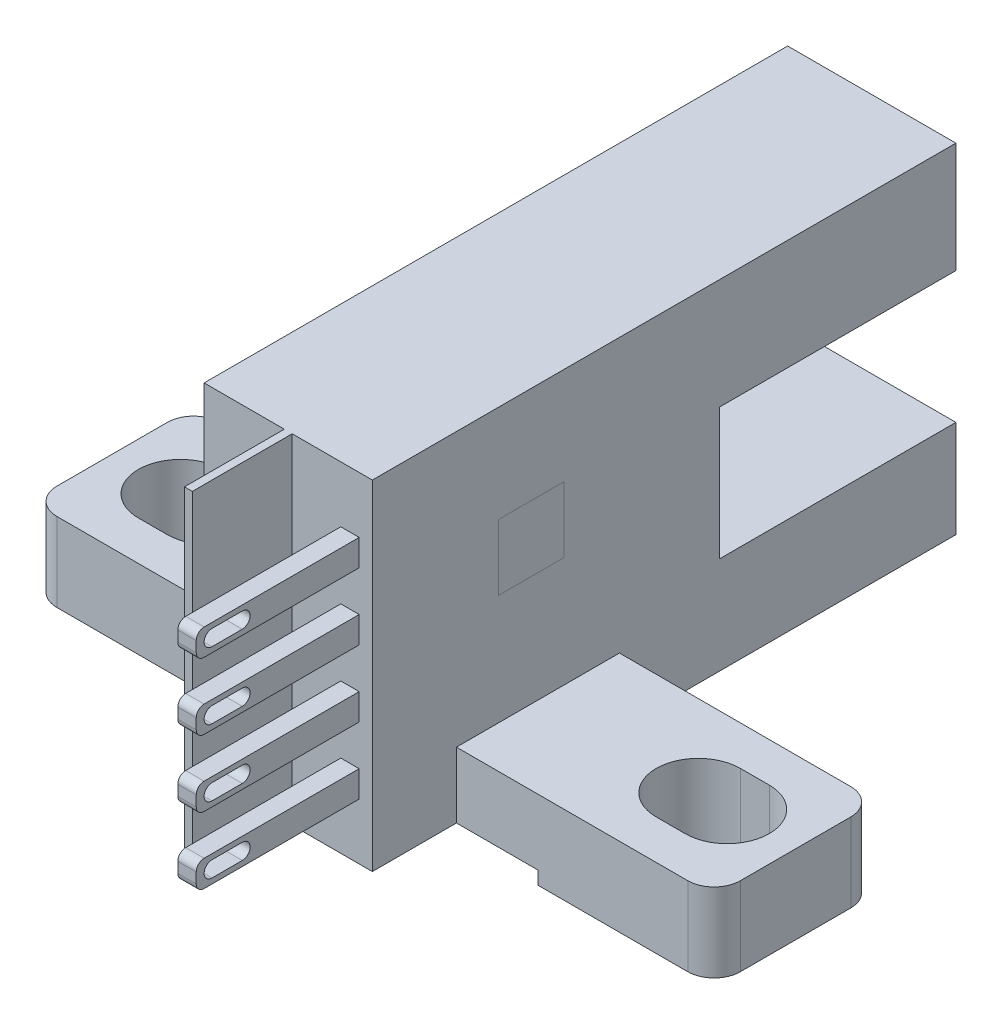
SolidWorks part; units mm, degrees
ref_plane "Front" through (0, 0, 0) normal (0, 0, 1) x (1, 0, 0)
ref_plane "Top" through (0, 0, 0) normal (0, 1, 0) x (1, 0, 0)
ref_plane "Right" through (0, 0, 0) normal (1, 0, 0) x (0, 0, -1)
sketch "Sketch2" plane through (0, 0, 0) normal (0, 1, 0) x (1, 0, 0)
  line L0 (-10.4, 0) -> (-9.3, 0) construction
  line L1 (13, -3.1) -> (-13, -3.1)
  line L2 (13, -3.1) -> (13, 3.1)
  line L3 (13, 3.1) -> (-13, 3.1)
  line L4 (-13, -3.1) -> (-13, 3.1)
  line L5 (13, -3.1) -> (-13, 3.1) construction
  line L6 (13, 3.1) -> (-13, -3.1) construction
  line L7 (-10.4, 1.6) -> (-9.3, 1.6)
  line L8 (-10.4, -1.6) -> (-9.3, -1.6)
  line L9 (0, 3.1) -> (0, 0) construction
  line L10 (10.4, 0) -> (9.3, 0) construction
  line L11 (10.4, 1.6) -> (9.3, 1.6)
  line L12 (10.4, -1.6) -> (9.3, -1.6)
  arc A0 (-10.4, 1.6) -> (-10.4, -1.6) centre (-10.4, 0) ccw
  arc A1 (-9.3, -1.6) -> (-9.3, 1.6) centre (-9.3, 0) ccw
  arc A2 (10.4, 1.6) -> (10.4, -1.6) centre (10.4, 0) cw
  arc A3 (9.3, -1.6) -> (9.3, 1.6) centre (9.3, 0) cw
  point P0 (0, 0)
  point P8 (-9.85, 0)
  point P13 (-7.7, 0)
  point P14 (-12, 0)
  point P19 (9.85, 0)
  dimension "D3" = 1.6
  dimension "D1" = 26
  dimension "D2" = 6.2
  dimension "D4" = 4.3
  dimension "D5" = 12
extrude "Boss-Extrude1" add sketch "Sketch2" along normal blind 3
sketch "Sketch3" plane through (0, 0, 0) normal (0, 1, 0) x (1, 0, 0)
  line L0 (13, -3.1) -> (13, 3.1) construction
  line L1 (-3.2, 15.9) -> (3.2, 15.9)
  line L2 (-3.2, 15.9) -> (-3.2, -6.3)
  line L3 (-3.2, -6.3) -> (3.2, -6.3)
  line L4 (3.2, 15.9) -> (3.2, -6.3)
  line L5 (-3.2, 15.9) -> (3.2, -6.3) construction
  line L6 (-3.2, -6.3) -> (3.2, 15.9) construction
  point P0 (0, 4.8)
  point P5 (0, 0)
  point P9 (13, 0)
  dimension "D1" = 6.4
  dimension "D2" = 22.2
  dimension "D3" = 6.3
extrude "Boss-Extrude2" add sketch "Sketch3" along normal blind 13.4
sketch "Sketch4" plane through (3.2, 0, 0) normal (1, 0, 0) x (0, 0, -1)
  line L0 (15.9, 13.4) -> (15.9, 0) construction
  line L1 (6.9, 4.2) -> (15.9, 4.2)
  line L2 (6.9, 4.2) -> (6.9, 9.2)
  line L3 (6.9, 9.2) -> (15.9, 9.2)
  line L4 (15.9, 4.2) -> (15.9, 9.2)
  line L5 (6.9, 4.2) -> (15.9, 9.2) construction
  line L6 (6.9, 9.2) -> (15.9, 4.2) construction
  line L7 (-6.3, 13.4) -> (-6.3, 0) construction
  point P0 (11.4, 6.7)
  point P7 (0, 0)
  point P10 (-6.3, 6.7)
  dimension "D1" = 5
  dimension "D2" = 9
extrude "Cut-Extrude1" cut sketch "Sketch4" against normal through all
sketch "Sketch5" plane through (3.2, 0, 0) normal (1, 0, 0) x (0, 0, -1)
  line L0 (6.9, 9.2) -> (6.9, 4.2) construction
  line L1 (1, 9.7) -> (-1.5, 9.7)
  line L2 (1, 9.7) -> (1, 7.2)
  line L3 (1, 7.2) -> (-1.5, 7.2)
  line L4 (-1.5, 9.7) -> (-1.5, 7.2)
  point P6 (6.9, 6.7)
  dimension "D1" = 2.5
  dimension "D2" = 8.4
  dimension "D3" = 3
split line "Split Line1"
fillet "Fillet1" radius 1 4 edges at (-13, 1.5, -3.1) (-13, 1.5, 3.1) (13, 1.5, -3.1) (13, 1.5, 3.1)
sketch "Sketch6" plane through (0, 0, 0) normal (0, 0, 1) x (1, 0, 0)
  line L0 (-12, 0) -> (-3.2, 0) construction
  line L1 (6.3, 0.5) -> (-6.3, 0.5)
  line L2 (6.3, 0.5) -> (6.3, 0)
  line L3 (6.3, 0) -> (-6.3, 0)
  line L4 (-6.3, 0.5) -> (-6.3, 0)
  line L5 (6.3, 0.5) -> (-6.3, 0) construction
  line L6 (6.3, 0) -> (-6.3, 0.5) construction
  point P0 (0, 0.25)
  point P7 (0, 0)
  dimension "D1" = 12.6
  dimension "D2" = 0.5
extrude "Cut-Extrude2" cut sketch "Sketch6" against normal through all both and the other way through all
sketch "Sketch8" plane through (0, 13.4, 0) normal (0, 1, 0) x (1, 0, 0)
  line L0 (-3.2, -6.3) -> (3.2, -6.3) construction
  line L1 (-0.15, -10.1) -> (0.15, -10.1)
  line L2 (-0.15, -10.1) -> (-0.15, -6.3)
  line L3 (-0.15, -6.3) -> (0.15, -6.3)
  line L4 (0.15, -10.1) -> (0.15, -6.3)
  line L5 (-0.15, -10.1) -> (0.15, -6.3) construction
  line L6 (-0.15, -6.3) -> (0.15, -10.1) construction
  point P0 (0, -8.2)
  point P7 (0, 0)
  point P8 (0, 0)
  dimension "D1" = 0.3
  dimension "D2" = 3.8
extrude "Boss-Extrude4" add sketch "Sketch8" against normal up to surface (12.9 mm away) up to face at (0, 0.5, -1.6)
sketch "Sketch9" plane through (3.2, 0, 0) normal (1, 0, 0) x (0, 0, -1)
  line L0 (-6.3, 6.95) -> (6.9, 6.95) construction
  line L1 (-6.3, 7.72) -> (-12.2, 7.72)
  line L2 (-6.3, 13.4) -> (-6.3, 0.5) construction
  line L3 (6.9, 9.2) -> (6.9, 4.2) construction
  line L4 (-6.3, 0.5) -> (-6.3, 13.4) construction
  line L5 (-6.3, 10.26) -> (-12.2, 10.26)
  line L6 (-6.3, 10.26) -> (-6.3, 11.26)
  line L7 (-6.3, 11.26) -> (-12.2, 11.26)
  line L8 (-12.5, 10.56) -> (-12.5, 10.96)
  line L9 (-11.9, 10.76) -> (-10.7496, 10.76) construction
  line L22 (-11.9, 11.06) -> (-10.7496, 11.06)
  line L23 (-11.9, 10.46) -> (-10.7496, 10.46)
  line L24 (-6.3, 7.72) -> (-6.3, 8.72)
  line L25 (-6.3, 8.72) -> (-12.2, 8.72)
  line L26 (-12.5, 8.02) -> (-12.5, 8.42)
  line L27 (-11.9, 8.22) -> (-10.7496, 8.22) construction
  line L28 (-11.9, 8.52) -> (-10.7496, 8.52)
  line L29 (-11.9, 7.92) -> (-10.7496, 7.92)
  line L30 (-6.3, 5.18) -> (-12.2, 5.18)
  line L31 (-6.3, 5.18) -> (-6.3, 6.18)
  line L32 (-6.3, 6.18) -> (-12.2, 6.18)
  line L33 (-12.5, 5.48) -> (-12.5, 5.88)
  line L34 (-11.9, 5.68) -> (-10.7496, 5.68) construction
  line L35 (-11.9, 5.98) -> (-10.7496, 5.98)
  line L36 (-11.9, 5.38) -> (-10.7496, 5.38)
  line L37 (-6.3, 2.64) -> (-12.2, 2.64)
  line L38 (-6.3, 2.64) -> (-6.3, 3.64)
  line L39 (-6.3, 3.64) -> (-12.2, 3.64)
  line L40 (-12.5, 2.94) -> (-12.5, 3.34)
  line L41 (-11.9, 3.14) -> (-10.7496, 3.14) construction
  line L42 (-11.9, 3.44) -> (-10.7496, 3.44)
  line L43 (-11.9, 2.84) -> (-10.7496, 2.84)
  arc A0 (-11.9, 11.06) -> (-11.9, 10.46) centre (-11.9, 10.76) ccw
  arc A1 (-10.7496, 10.46) -> (-10.7496, 11.06) centre (-10.7496, 10.76) ccw
  arc A2 (-12.2, 10.26) -> (-12.5, 10.56) centre (-12.2, 10.56) cw
  arc A3 (-12.2, 11.26) -> (-12.5, 10.96) centre (-12.2, 10.96) ccw
  arc A4 (-12.2, 7.72) -> (-12.5, 8.02) centre (-12.2, 8.02) cw
  arc A5 (-12.2, 8.72) -> (-12.5, 8.42) centre (-12.2, 8.42) ccw
  arc A6 (-11.9, 8.52) -> (-11.9, 7.92) centre (-11.9, 8.22) ccw
  arc A7 (-10.7496, 7.92) -> (-10.7496, 8.52) centre (-10.7496, 8.22) ccw
  arc A8 (-12.2, 5.18) -> (-12.5, 5.48) centre (-12.2, 5.48) cw
  arc A9 (-12.2, 6.18) -> (-12.5, 5.88) centre (-12.2, 5.88) ccw
  arc A10 (-11.9, 5.98) -> (-11.9, 5.38) centre (-11.9, 5.68) ccw
  arc A11 (-10.7496, 5.38) -> (-10.7496, 5.98) centre (-10.7496, 5.68) ccw
  arc A12 (-12.2, 2.64) -> (-12.5, 2.94) centre (-12.2, 2.94) cw
  arc A13 (-12.2, 3.64) -> (-12.5, 3.34) centre (-12.2, 3.34) ccw
  arc A14 (-11.9, 3.44) -> (-11.9, 2.84) centre (-11.9, 3.14) ccw
  arc A15 (-10.7496, 2.84) -> (-10.7496, 3.44) centre (-10.7496, 3.14) ccw
  point P12 (-12.2, 10.76)
  point P20 (-11.3248, 8.22)
  point P26 (-11.3248, 10.76)
  point P31 (-12.5, 10.76)
  point P47 (-11.3248, 5.68)
  point P62 (-11.3248, 3.14)
  dimension "D6" = 0.3
  dimension "D7" = 0.3
  dimension "D1" = 1
  dimension "D2" = 6.2
  dimension "D3" = 1.1504
  dimension "D4" = 0.3
  dimension "D5" = 4
extrude "Boss-Extrude5" add sketch "Sketch9" against normal blind 0.7 from offset 0.5 offset against normal yes
sketch "Sketch10" plane through (0, 0, -15.9) normal (0, 0, -1) x (-1, 0, 0)
  line L0 (0, 9.2) -> (0, 13.4) construction
  line L1 (-3.2, 9.2) -> (3.2, 9.2) construction
  line L2 (-3.2, 13.4) -> (3.2, 13.4) construction
  line L3 (0, 10.2975) -> (-1.0415, 12.0869)
  line L4 (-1.0415, 12.0869) -> (1.0415, 12.0869)
  line L5 (0, 10.2975) -> (1.0415, 12.0869)
  line L6 (0, 4.2) -> (0, 0.5) construction
  line L7 (3.2, 4.2) -> (-3.2, 4.2) construction
  line L8 (-3.2, 0.5) -> (3.2, 0.5) construction
  line L9 (1.0415, 3.0346) -> (-1.0415, 3.0346)
  line L10 (-1.0415, 3.0346) -> (0, 1.4471)
  line L11 (1.0415, 3.0346) -> (0, 1.4471)
  point P10 (0, 12.0869)
  point P20 (0, 3.0346)
extrude "Cut-Extrude3" cut sketch "Sketch10" against normal blind 0.2
